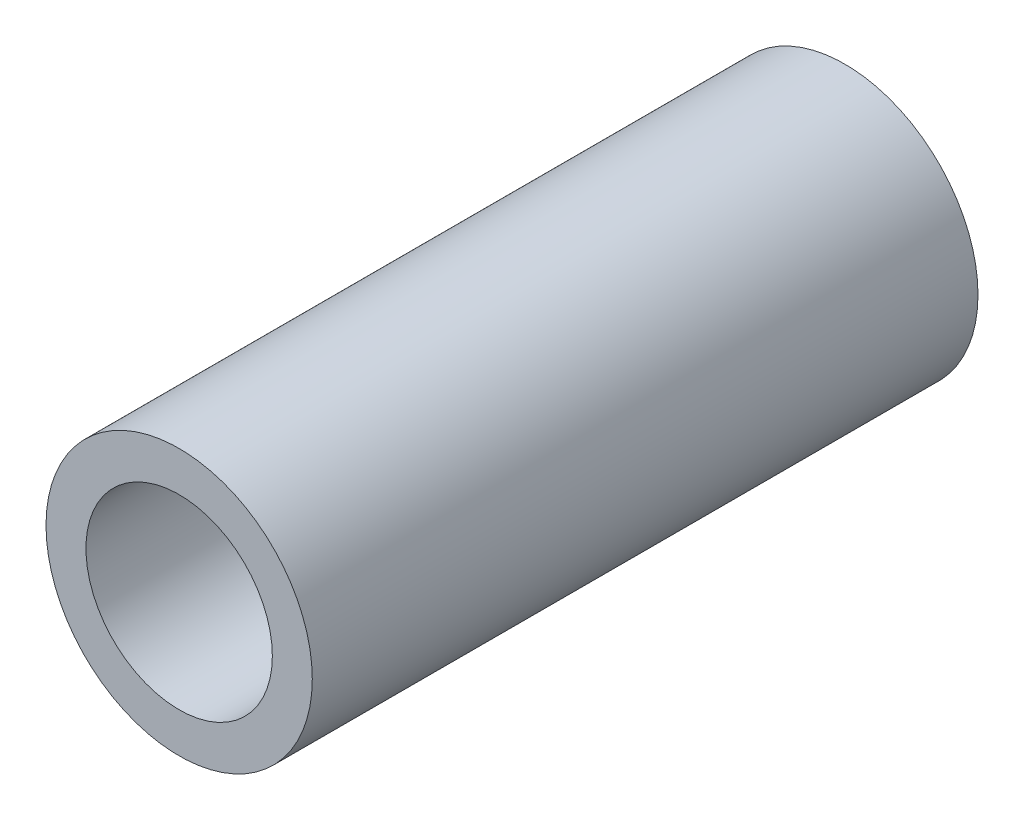
SolidWorks part; units mm, degrees
ref_plane "前视基准面" through (0, 0, 0) normal (0, 0, 1) x (1, 0, 0)
ref_plane "上视基准面" through (0, 0, 0) normal (0, 1, 0) x (1, 0, 0)
ref_plane "右视基准面" through (0, 0, 0) normal (1, 0, 0) x (0, 0, -1)
other "Configuration Table"
sketch "草图1" plane through (0, 0, 0) normal (0, 0, 1) x (1, 0, 0)
  circle A0 centre (0, 0) radius 2
  circle A1 centre (0, 0) radius 1.4
  dimension "D1" = 4
  dimension "D2" = 2.8
extrude "凸台-拉伸1" add sketch "草图1" along normal blind 10
